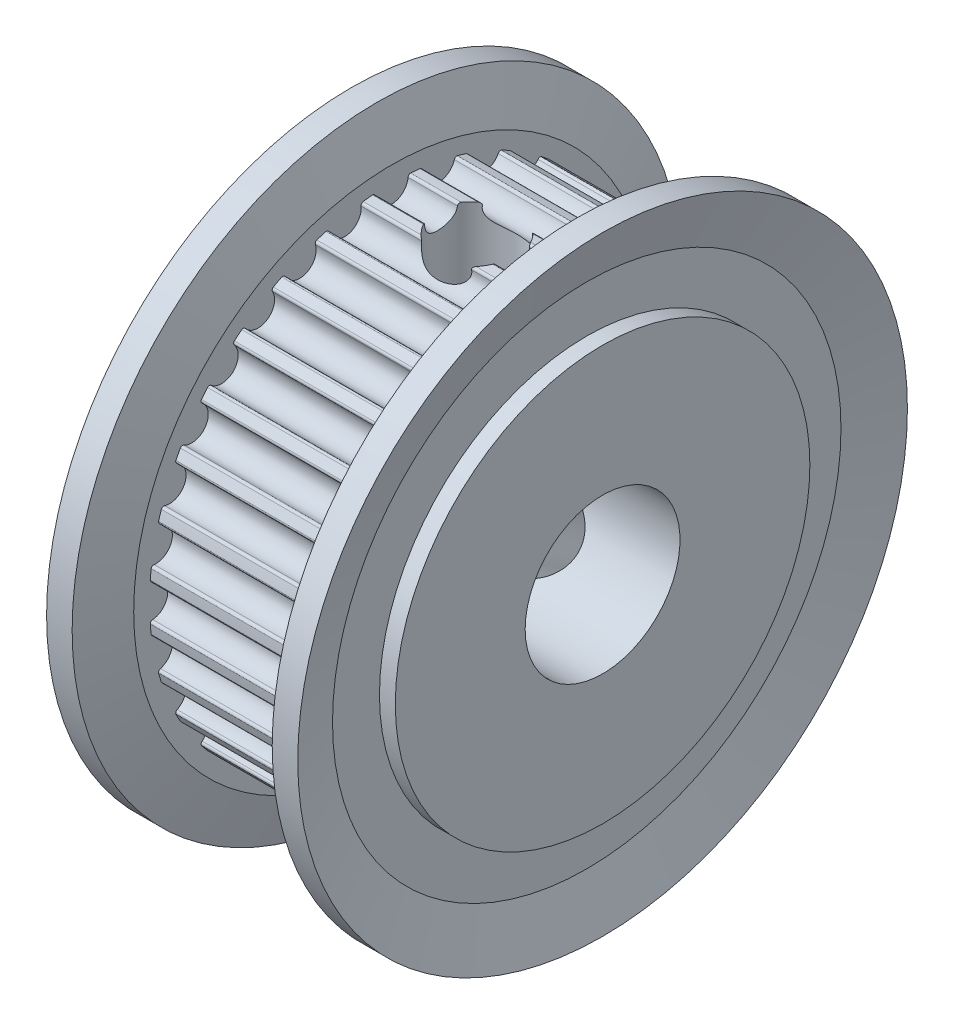
SolidWorks part; units mm, degrees
ref_plane "Front Plane" through (0, 0, 0) normal (0, 0, 1) x (1, 0, 0)
ref_plane "Top Plane" through (0, 0, 0) normal (0, 1, 0) x (1, 0, 0)
ref_plane "Right Plane" through (0, 0, 0) normal (1, 0, 0) x (0, 0, -1)
ref_plane "Plane1" through (0, 0, 0) normal (0, 0, 1) x (1, 0, 0)
sketch "Sketch1" plane through (0, 0, 0) normal (0, 0, 1) x (1, 0, 0)
  line L0 (-5.15, 0) -> (-5.15, 8.5)
  line L1 (-5.15, 8.5) -> (-3.5, 8.5)
  line L2 (-3.5, 8.5) -> (-3.5, 9.93)
  line L3 (-3.5, 9.93) -> (3.5, 9.93)
  line L4 (3.5, 9.93) -> (3.5, 8.5)
  line L5 (3.5, 8.5) -> (5.15, 8.5)
  line L6 (5.15, 8.5) -> (5.15, 0)
  line L7 (5.15, 0) -> (-5.15, 0)
  line L8 (5.15, 0) -> (-5.15, 0) construction
revolve "Revolve1" add sketch "Sketch1" angle 360 about L8
ref_plane "Plane2" through (0, 0, 0) normal (1, 0, 0) x (0, 0, -1)
sketch "Sketch2" plane through (0, 0, 0) normal (1, 0, 0) x (0, 0, -1)
  line L0 (-0.9509, 10.1405) -> (-0.9273, 9.8885)
  line L1 (-0.9273, 9.8885) -> (-0.793, 9.8993)
  line L2 (0.793, 9.8993) -> (0.9273, 9.8885)
  line L3 (0.9273, 9.8885) -> (0.9509, 10.1405)
  arc A0 (-0.793, 9.8993) -> (-0.6724, 9.7974) centre (-0.784, 9.7876) cw
  arc A1 (-0.6724, 9.7974) -> (0.6724, 9.7974) centre (0, 9.856) ccw
  arc A2 (0.6724, 9.7974) -> (0.793, 9.8993) centre (0.784, 9.7876) cw
  arc A3 (0.9509, 10.1405) -> (-0.9509, 10.1405) centre (0, 0) ccw
extrude "Cut-Extrude1" cut sketch "Sketch2" against normal blind 3.5 and the other way blind 3.5
ref_plane "Plane3" through (0, 0, 0) normal (1, 0, 0) x (0, 0, -1)
sketch "Sketch3" plane through (0, 0, 0) normal (1, 0, 0) x (0, 0, -1)
  line L0 (-2.911, 9.7602) -> (-2.8386, 9.5176)
  line L1 (-2.8386, 9.5176) -> (-2.709, 9.5544)
  line L2 (-1.1535, 9.8638) -> (-1.0197, 9.8794)
  line L3 (-1.0197, 9.8794) -> (-1.0457, 10.1312)
  arc A0 (-2.709, 9.5544) -> (-2.5709, 9.4779) centre (-2.6784, 9.4466) cw
  arc A1 (-2.5709, 9.4779) -> (-1.2518, 9.7403) centre (-1.9228, 9.6666) ccw
  arc A2 (-1.2518, 9.7403) -> (-1.1535, 9.8638) centre (-1.1405, 9.7525) cw
  arc A3 (-1.0457, 10.1312) -> (-2.911, 9.7602) centre (0, 0) ccw
extrude "Cut-Extrude2" cut sketch "Sketch3" against normal blind 3.5 and the other way blind 3.5
ref_plane "Plane4" through (0, 0, 0) normal (1, 0, 0) x (0, 0, -1)
sketch "Sketch4" plane through (0, 0, 0) normal (1, 0, 0) x (0, 0, -1)
  line L0 (-4.7591, 9.0047) -> (-4.6409, 8.781)
  line L1 (-4.6409, 8.781) -> (-4.5209, 8.8423)
  line L2 (-3.0557, 9.4492) -> (-2.9275, 9.4907)
  line L3 (-2.9275, 9.4907) -> (-3.0021, 9.7325)
  arc A0 (-4.5209, 8.8423) -> (-4.3706, 8.7943) centre (-4.4699, 8.7426) cw
  arc A1 (-4.3706, 8.7943) -> (-3.128, 9.3089) centre (-3.7717, 9.1058) ccw
  arc A2 (-3.128, 9.3089) -> (-3.0557, 9.4492) centre (-3.0212, 9.3426) cw
  arc A3 (-3.0021, 9.7325) -> (-4.7591, 9.0047) centre (0, 0) ccw
extrude "Cut-Extrude3" cut sketch "Sketch4" against normal blind 3.5 and the other way blind 3.5
ref_plane "Plane5" through (0, 0, 0) normal (1, 0, 0) x (0, 0, -1)
sketch "Sketch5" plane through (0, 0, 0) normal (1, 0, 0) x (0, 0, -1)
  line L0 (-6.4244, 7.9032) -> (-6.2648, 7.7068)
  line L1 (-6.2648, 7.7068) -> (-6.1591, 7.7904)
  line L2 (-4.8404, 8.6715) -> (-4.7228, 8.7372)
  line L3 (-4.7228, 8.7372) -> (-4.8431, 8.9598)
  arc A0 (-6.1591, 7.7904) -> (-6.0023, 7.7726) centre (-6.0896, 7.7026) cw
  arc A1 (-6.0023, 7.7726) -> (-4.884, 8.5198) centre (-5.4757, 8.195) ccw
  arc A2 (-4.884, 8.5198) -> (-4.8404, 8.6715) centre (-4.7858, 8.5737) cw
  arc A3 (-4.8431, 8.9598) -> (-6.4244, 7.9032) centre (0, 0) ccw
extrude "Cut-Extrude4" cut sketch "Sketch5" against normal blind 3.5 and the other way blind 3.5
ref_plane "Plane6" through (0, 0, 0) normal (1, 0, 0) x (0, 0, -1)
sketch "Sketch6" plane through (0, 0, 0) normal (1, 0, 0) x (0, 0, -1)
  line L0 (-7.8428, 6.498) -> (-7.6479, 6.3366)
  line L1 (-7.6479, 6.3366) -> (-7.5606, 6.4391)
  line L2 (-6.4391, 7.5606) -> (-6.3366, 7.6479)
  line L3 (-6.3366, 7.6479) -> (-6.498, 7.8428)
  arc A0 (-7.5606, 6.4391) -> (-7.4033, 6.4523) centre (-7.4753, 6.3665) cw
  arc A1 (-7.4033, 6.4523) -> (-6.4523, 7.4033) centre (-6.9692, 6.9692) ccw
  arc A2 (-6.4523, 7.4033) -> (-6.4391, 7.5606) centre (-6.3665, 7.4753) cw
  arc A3 (-6.498, 7.8428) -> (-7.8428, 6.498) centre (0, 0) ccw
extrude "Cut-Extrude5" cut sketch "Sketch6" against normal blind 3.5 and the other way blind 3.5
ref_plane "Plane7" through (0, 0, 0) normal (1, 0, 0) x (0, 0, -1)
sketch "Sketch7" plane through (0, 0, 0) normal (1, 0, 0) x (0, 0, -1)
  line L0 (-8.9598, 4.8431) -> (-8.7372, 4.7228)
  line L1 (-8.7372, 4.7228) -> (-8.6715, 4.8404)
  line L2 (-7.7904, 6.1591) -> (-7.7068, 6.2648)
  line L3 (-7.7068, 6.2648) -> (-7.9032, 6.4244)
  arc A0 (-8.6715, 4.8404) -> (-8.5198, 4.884) centre (-8.5737, 4.7858) cw
  arc A1 (-8.5198, 4.884) -> (-7.7726, 6.0023) centre (-8.195, 5.4757) ccw
  arc A2 (-7.7726, 6.0023) -> (-7.7904, 6.1591) centre (-7.7026, 6.0896) cw
  arc A3 (-7.9032, 6.4244) -> (-8.9598, 4.8431) centre (0, 0) ccw
extrude "Cut-Extrude6" cut sketch "Sketch7" against normal blind 3.5 and the other way blind 3.5
ref_plane "Plane8" through (0, 0, 0) normal (1, 0, 0) x (0, 0, -1)
sketch "Sketch8" plane through (0, 0, 0) normal (1, 0, 0) x (0, 0, -1)
  line L0 (-9.7325, 3.0021) -> (-9.4907, 2.9275)
  line L1 (-9.4907, 2.9275) -> (-9.4492, 3.0557)
  line L2 (-8.8423, 4.5209) -> (-8.781, 4.6409)
  line L3 (-8.781, 4.6409) -> (-9.0047, 4.7591)
  arc A0 (-9.4492, 3.0557) -> (-9.3089, 3.128) centre (-9.3426, 3.0212) cw
  arc A1 (-9.3089, 3.128) -> (-8.7943, 4.3706) centre (-9.1058, 3.7717) ccw
  arc A2 (-8.7943, 4.3706) -> (-8.8423, 4.5209) centre (-8.7426, 4.4699) cw
  arc A3 (-9.0047, 4.7591) -> (-9.7325, 3.0021) centre (0, 0) ccw
extrude "Cut-Extrude7" cut sketch "Sketch8" against normal blind 3.5 and the other way blind 3.5
ref_plane "Plane9" through (0, 0, 0) normal (1, 0, 0) x (0, 0, -1)
sketch "Sketch9" plane through (0, 0, 0) normal (1, 0, 0) x (0, 0, -1)
  line L0 (-10.1312, 1.0457) -> (-9.8794, 1.0197)
  line L1 (-9.8794, 1.0197) -> (-9.8638, 1.1535)
  line L2 (-9.5544, 2.709) -> (-9.5176, 2.8386)
  line L3 (-9.5176, 2.8386) -> (-9.7602, 2.911)
  arc A0 (-9.8638, 1.1535) -> (-9.7403, 1.2518) centre (-9.7525, 1.1405) cw
  arc A1 (-9.7403, 1.2518) -> (-9.4779, 2.5709) centre (-9.6666, 1.9228) ccw
  arc A2 (-9.4779, 2.5709) -> (-9.5544, 2.709) centre (-9.4466, 2.6784) cw
  arc A3 (-9.7602, 2.911) -> (-10.1312, 1.0457) centre (0, 0) ccw
extrude "Cut-Extrude8" cut sketch "Sketch9" against normal blind 3.5 and the other way blind 3.5
ref_plane "Plane10" through (0, 0, 0) normal (1, 0, 0) x (0, 0, -1)
sketch "Sketch10" plane through (0, 0, 0) normal (1, 0, 0) x (0, 0, -1)
  line L0 (-10.1405, -0.9509) -> (-9.8885, -0.9273)
  line L1 (-9.8885, -0.9273) -> (-9.8993, -0.793)
  line L2 (-9.8993, 0.793) -> (-9.8885, 0.9273)
  line L3 (-9.8885, 0.9273) -> (-10.1405, 0.9509)
  arc A0 (-9.8993, -0.793) -> (-9.7974, -0.6724) centre (-9.7876, -0.784) cw
  arc A1 (-9.7974, -0.6724) -> (-9.7974, 0.6724) centre (-9.856, 0) ccw
  arc A2 (-9.7974, 0.6724) -> (-9.8993, 0.793) centre (-9.7876, 0.784) cw
  arc A3 (-10.1405, 0.9509) -> (-10.1405, -0.9509) centre (0, 0) ccw
extrude "Cut-Extrude9" cut sketch "Sketch10" against normal blind 3.5 and the other way blind 3.5
ref_plane "Plane11" through (0, 0, 0) normal (1, 0, 0) x (0, 0, -1)
sketch "Sketch11" plane through (0, 0, 0) normal (1, 0, 0) x (0, 0, -1)
  line L0 (-9.7602, -2.911) -> (-9.5176, -2.8386)
  line L1 (-9.5176, -2.8386) -> (-9.5544, -2.709)
  line L2 (-9.8638, -1.1535) -> (-9.8794, -1.0197)
  line L3 (-9.8794, -1.0197) -> (-10.1312, -1.0457)
  arc A0 (-9.5544, -2.709) -> (-9.4779, -2.5709) centre (-9.4466, -2.6784) cw
  arc A1 (-9.4779, -2.5709) -> (-9.7403, -1.2518) centre (-9.6666, -1.9228) ccw
  arc A2 (-9.7403, -1.2518) -> (-9.8638, -1.1535) centre (-9.7525, -1.1405) cw
  arc A3 (-10.1312, -1.0457) -> (-9.7602, -2.911) centre (0, 0) ccw
extrude "Cut-Extrude10" cut sketch "Sketch11" against normal blind 3.5 and the other way blind 3.5
ref_plane "Plane12" through (0, 0, 0) normal (1, 0, 0) x (0, 0, -1)
sketch "Sketch12" plane through (0, 0, 0) normal (1, 0, 0) x (0, 0, -1)
  line L0 (-9.0047, -4.7591) -> (-8.781, -4.6409)
  line L1 (-8.781, -4.6409) -> (-8.8423, -4.5209)
  line L2 (-9.4492, -3.0557) -> (-9.4907, -2.9275)
  line L3 (-9.4907, -2.9275) -> (-9.7325, -3.0021)
  arc A0 (-8.8423, -4.5209) -> (-8.7943, -4.3706) centre (-8.7426, -4.4699) cw
  arc A1 (-8.7943, -4.3706) -> (-9.3089, -3.128) centre (-9.1058, -3.7717) ccw
  arc A2 (-9.3089, -3.128) -> (-9.4492, -3.0557) centre (-9.3426, -3.0212) cw
  arc A3 (-9.7325, -3.0021) -> (-9.0047, -4.7591) centre (0, 0) ccw
extrude "Cut-Extrude11" cut sketch "Sketch12" against normal blind 3.5 and the other way blind 3.5
ref_plane "Plane13" through (0, 0, 0) normal (1, 0, 0) x (0, 0, -1)
sketch "Sketch13" plane through (0, 0, 0) normal (1, 0, 0) x (0, 0, -1)
  line L0 (-7.9032, -6.4244) -> (-7.7068, -6.2648)
  line L1 (-7.7068, -6.2648) -> (-7.7904, -6.1591)
  line L2 (-8.6715, -4.8404) -> (-8.7372, -4.7228)
  line L3 (-8.7372, -4.7228) -> (-8.9598, -4.8431)
  arc A0 (-7.7904, -6.1591) -> (-7.7726, -6.0023) centre (-7.7026, -6.0896) cw
  arc A1 (-7.7726, -6.0023) -> (-8.5198, -4.884) centre (-8.195, -5.4757) ccw
  arc A2 (-8.5198, -4.884) -> (-8.6715, -4.8404) centre (-8.5737, -4.7858) cw
  arc A3 (-8.9598, -4.8431) -> (-7.9032, -6.4244) centre (0, 0) ccw
extrude "Cut-Extrude12" cut sketch "Sketch13" against normal blind 3.5 and the other way blind 3.5
ref_plane "Plane14" through (0, 0, 0) normal (1, 0, 0) x (0, 0, -1)
sketch "Sketch14" plane through (0, 0, 0) normal (1, 0, 0) x (0, 0, -1)
  line L0 (-6.498, -7.8428) -> (-6.3366, -7.6479)
  line L1 (-6.3366, -7.6479) -> (-6.4391, -7.5606)
  line L2 (-7.5606, -6.4391) -> (-7.6479, -6.3366)
  line L3 (-7.6479, -6.3366) -> (-7.8428, -6.498)
  arc A0 (-6.4391, -7.5606) -> (-6.4523, -7.4033) centre (-6.3665, -7.4753) cw
  arc A1 (-6.4523, -7.4033) -> (-7.4033, -6.4523) centre (-6.9692, -6.9692) ccw
  arc A2 (-7.4033, -6.4523) -> (-7.5606, -6.4391) centre (-7.4753, -6.3665) cw
  arc A3 (-7.8428, -6.498) -> (-6.498, -7.8428) centre (0, 0) ccw
extrude "Cut-Extrude13" cut sketch "Sketch14" against normal blind 3.5 and the other way blind 3.5
ref_plane "Plane15" through (0, 0, 0) normal (1, 0, 0) x (0, 0, -1)
sketch "Sketch15" plane through (0, 0, 0) normal (1, 0, 0) x (0, 0, -1)
  line L0 (-4.8431, -8.9598) -> (-4.7228, -8.7372)
  line L1 (-4.7228, -8.7372) -> (-4.8404, -8.6715)
  line L2 (-6.1591, -7.7904) -> (-6.2648, -7.7068)
  line L3 (-6.2648, -7.7068) -> (-6.4244, -7.9032)
  arc A0 (-4.8404, -8.6715) -> (-4.884, -8.5198) centre (-4.7858, -8.5737) cw
  arc A1 (-4.884, -8.5198) -> (-6.0023, -7.7726) centre (-5.4757, -8.195) ccw
  arc A2 (-6.0023, -7.7726) -> (-6.1591, -7.7904) centre (-6.0896, -7.7026) cw
  arc A3 (-6.4244, -7.9032) -> (-4.8431, -8.9598) centre (0, 0) ccw
extrude "Cut-Extrude14" cut sketch "Sketch15" against normal blind 3.5 and the other way blind 3.5
ref_plane "Plane16" through (0, 0, 0) normal (1, 0, 0) x (0, 0, -1)
sketch "Sketch16" plane through (0, 0, 0) normal (1, 0, 0) x (0, 0, -1)
  line L0 (-3.0021, -9.7325) -> (-2.9275, -9.4907)
  line L1 (-2.9275, -9.4907) -> (-3.0557, -9.4492)
  line L2 (-4.5209, -8.8423) -> (-4.6409, -8.781)
  line L3 (-4.6409, -8.781) -> (-4.7591, -9.0047)
  arc A0 (-3.0557, -9.4492) -> (-3.128, -9.3089) centre (-3.0212, -9.3426) cw
  arc A1 (-3.128, -9.3089) -> (-4.3706, -8.7943) centre (-3.7717, -9.1058) ccw
  arc A2 (-4.3706, -8.7943) -> (-4.5209, -8.8423) centre (-4.4699, -8.7426) cw
  arc A3 (-4.7591, -9.0047) -> (-3.0021, -9.7325) centre (0, 0) ccw
extrude "Cut-Extrude15" cut sketch "Sketch16" against normal blind 3.5 and the other way blind 3.5
ref_plane "Plane17" through (0, 0, 0) normal (1, 0, 0) x (0, 0, -1)
sketch "Sketch17" plane through (0, 0, 0) normal (1, 0, 0) x (0, 0, -1)
  line L0 (-1.0457, -10.1312) -> (-1.0197, -9.8794)
  line L1 (-1.0197, -9.8794) -> (-1.1535, -9.8638)
  line L2 (-2.709, -9.5544) -> (-2.8386, -9.5176)
  line L3 (-2.8386, -9.5176) -> (-2.911, -9.7602)
  arc A0 (-1.1535, -9.8638) -> (-1.2518, -9.7403) centre (-1.1405, -9.7525) cw
  arc A1 (-1.2518, -9.7403) -> (-2.5709, -9.4779) centre (-1.9228, -9.6666) ccw
  arc A2 (-2.5709, -9.4779) -> (-2.709, -9.5544) centre (-2.6784, -9.4466) cw
  arc A3 (-2.911, -9.7602) -> (-1.0457, -10.1312) centre (0, 0) ccw
extrude "Cut-Extrude16" cut sketch "Sketch17" against normal blind 3.5 and the other way blind 3.5
ref_plane "Plane18" through (0, 0, 0) normal (1, 0, 0) x (0, 0, -1)
sketch "Sketch18" plane through (0, 0, 0) normal (1, 0, 0) x (0, 0, -1)
  line L0 (0.9509, -10.1405) -> (0.9273, -9.8885)
  line L1 (0.9273, -9.8885) -> (0.793, -9.8993)
  line L2 (-0.793, -9.8993) -> (-0.9273, -9.8885)
  line L3 (-0.9273, -9.8885) -> (-0.9509, -10.1405)
  arc A0 (0.793, -9.8993) -> (0.6724, -9.7974) centre (0.784, -9.7876) cw
  arc A1 (0.6724, -9.7974) -> (-0.6724, -9.7974) centre (0, -9.856) ccw
  arc A2 (-0.6724, -9.7974) -> (-0.793, -9.8993) centre (-0.784, -9.7876) cw
  arc A3 (-0.9509, -10.1405) -> (0.9509, -10.1405) centre (0, 0) ccw
extrude "Cut-Extrude17" cut sketch "Sketch18" against normal blind 3.5 and the other way blind 3.5
ref_plane "Plane19" through (0, 0, 0) normal (1, 0, 0) x (0, 0, -1)
sketch "Sketch19" plane through (0, 0, 0) normal (1, 0, 0) x (0, 0, -1)
  line L0 (2.911, -9.7602) -> (2.8386, -9.5176)
  line L1 (2.8386, -9.5176) -> (2.709, -9.5544)
  line L2 (1.1535, -9.8638) -> (1.0197, -9.8794)
  line L3 (1.0197, -9.8794) -> (1.0457, -10.1312)
  arc A0 (2.709, -9.5544) -> (2.5709, -9.4779) centre (2.6784, -9.4466) cw
  arc A1 (2.5709, -9.4779) -> (1.2518, -9.7403) centre (1.9228, -9.6666) ccw
  arc A2 (1.2518, -9.7403) -> (1.1535, -9.8638) centre (1.1405, -9.7525) cw
  arc A3 (1.0457, -10.1312) -> (2.911, -9.7602) centre (0, 0) ccw
extrude "Cut-Extrude18" cut sketch "Sketch19" against normal blind 3.5 and the other way blind 3.5
ref_plane "Plane20" through (0, 0, 0) normal (1, 0, 0) x (0, 0, -1)
sketch "Sketch20" plane through (0, 0, 0) normal (1, 0, 0) x (0, 0, -1)
  line L0 (4.7591, -9.0047) -> (4.6409, -8.781)
  line L1 (4.6409, -8.781) -> (4.5209, -8.8423)
  line L2 (3.0557, -9.4492) -> (2.9275, -9.4907)
  line L3 (2.9275, -9.4907) -> (3.0021, -9.7325)
  arc A0 (4.5209, -8.8423) -> (4.3706, -8.7943) centre (4.4699, -8.7426) cw
  arc A1 (4.3706, -8.7943) -> (3.128, -9.3089) centre (3.7717, -9.1058) ccw
  arc A2 (3.128, -9.3089) -> (3.0557, -9.4492) centre (3.0212, -9.3426) cw
  arc A3 (3.0021, -9.7325) -> (4.7591, -9.0047) centre (0, 0) ccw
extrude "Cut-Extrude19" cut sketch "Sketch20" against normal blind 3.5 and the other way blind 3.5
ref_plane "Plane21" through (0, 0, 0) normal (1, 0, 0) x (0, 0, -1)
sketch "Sketch21" plane through (0, 0, 0) normal (1, 0, 0) x (0, 0, -1)
  line L0 (6.4244, -7.9032) -> (6.2648, -7.7068)
  line L1 (6.2648, -7.7068) -> (6.1591, -7.7904)
  line L2 (4.8404, -8.6715) -> (4.7228, -8.7372)
  line L3 (4.7228, -8.7372) -> (4.8431, -8.9598)
  arc A0 (6.1591, -7.7904) -> (6.0023, -7.7726) centre (6.0896, -7.7026) cw
  arc A1 (6.0023, -7.7726) -> (4.884, -8.5198) centre (5.4757, -8.195) ccw
  arc A2 (4.884, -8.5198) -> (4.8404, -8.6715) centre (4.7858, -8.5737) cw
  arc A3 (4.8431, -8.9598) -> (6.4244, -7.9032) centre (0, 0) ccw
extrude "Cut-Extrude20" cut sketch "Sketch21" against normal blind 3.5 and the other way blind 3.5
ref_plane "Plane22" through (0, 0, 0) normal (1, 0, 0) x (0, 0, -1)
sketch "Sketch22" plane through (0, 0, 0) normal (1, 0, 0) x (0, 0, -1)
  line L0 (7.8428, -6.498) -> (7.6479, -6.3366)
  line L1 (7.6479, -6.3366) -> (7.5606, -6.4391)
  line L2 (6.4391, -7.5606) -> (6.3366, -7.6479)
  line L3 (6.3366, -7.6479) -> (6.498, -7.8428)
  arc A0 (7.5606, -6.4391) -> (7.4033, -6.4523) centre (7.4753, -6.3665) cw
  arc A1 (7.4033, -6.4523) -> (6.4523, -7.4033) centre (6.9692, -6.9692) ccw
  arc A2 (6.4523, -7.4033) -> (6.4391, -7.5606) centre (6.3665, -7.4753) cw
  arc A3 (6.498, -7.8428) -> (7.8428, -6.498) centre (0, 0) ccw
extrude "Cut-Extrude21" cut sketch "Sketch22" against normal blind 3.5 and the other way blind 3.5
ref_plane "Plane23" through (0, 0, 0) normal (1, 0, 0) x (0, 0, -1)
sketch "Sketch23" plane through (0, 0, 0) normal (1, 0, 0) x (0, 0, -1)
  line L0 (8.9598, -4.8431) -> (8.7372, -4.7228)
  line L1 (8.7372, -4.7228) -> (8.6715, -4.8404)
  line L2 (7.7904, -6.1591) -> (7.7068, -6.2648)
  line L3 (7.7068, -6.2648) -> (7.9032, -6.4244)
  arc A0 (8.6715, -4.8404) -> (8.5198, -4.884) centre (8.5737, -4.7858) cw
  arc A1 (8.5198, -4.884) -> (7.7726, -6.0023) centre (8.195, -5.4757) ccw
  arc A2 (7.7726, -6.0023) -> (7.7904, -6.1591) centre (7.7026, -6.0896) cw
  arc A3 (7.9032, -6.4244) -> (8.9598, -4.8431) centre (0, 0) ccw
extrude "Cut-Extrude22" cut sketch "Sketch23" against normal blind 3.5 and the other way blind 3.5
ref_plane "Plane24" through (0, 0, 0) normal (1, 0, 0) x (0, 0, -1)
sketch "Sketch24" plane through (0, 0, 0) normal (1, 0, 0) x (0, 0, -1)
  line L0 (9.7325, -3.0021) -> (9.4907, -2.9275)
  line L1 (9.4907, -2.9275) -> (9.4492, -3.0557)
  line L2 (8.8423, -4.5209) -> (8.781, -4.6409)
  line L3 (8.781, -4.6409) -> (9.0047, -4.7591)
  arc A0 (9.4492, -3.0557) -> (9.3089, -3.128) centre (9.3426, -3.0212) cw
  arc A1 (9.3089, -3.128) -> (8.7943, -4.3706) centre (9.1058, -3.7717) ccw
  arc A2 (8.7943, -4.3706) -> (8.8423, -4.5209) centre (8.7426, -4.4699) cw
  arc A3 (9.0047, -4.7591) -> (9.7325, -3.0021) centre (0, 0) ccw
extrude "Cut-Extrude23" cut sketch "Sketch24" against normal blind 3.5 and the other way blind 3.5
ref_plane "Plane25" through (0, 0, 0) normal (1, 0, 0) x (0, 0, -1)
sketch "Sketch25" plane through (0, 0, 0) normal (1, 0, 0) x (0, 0, -1)
  line L0 (10.1312, -1.0457) -> (9.8794, -1.0197)
  line L1 (9.8794, -1.0197) -> (9.8638, -1.1535)
  line L2 (9.5544, -2.709) -> (9.5176, -2.8386)
  line L3 (9.5176, -2.8386) -> (9.7602, -2.911)
  arc A0 (9.8638, -1.1535) -> (9.7403, -1.2518) centre (9.7525, -1.1405) cw
  arc A1 (9.7403, -1.2518) -> (9.4779, -2.5709) centre (9.6666, -1.9228) ccw
  arc A2 (9.4779, -2.5709) -> (9.5544, -2.709) centre (9.4466, -2.6784) cw
  arc A3 (9.7602, -2.911) -> (10.1312, -1.0457) centre (0, 0) ccw
extrude "Cut-Extrude24" cut sketch "Sketch25" against normal blind 3.5 and the other way blind 3.5
ref_plane "Plane26" through (0, 0, 0) normal (1, 0, 0) x (0, 0, -1)
sketch "Sketch26" plane through (0, 0, 0) normal (1, 0, 0) x (0, 0, -1)
  line L0 (10.1405, 0.9509) -> (9.8885, 0.9273)
  line L1 (9.8885, 0.9273) -> (9.8993, 0.793)
  line L2 (9.8993, -0.793) -> (9.8885, -0.9273)
  line L3 (9.8885, -0.9273) -> (10.1405, -0.9509)
  arc A0 (9.8993, 0.793) -> (9.7974, 0.6724) centre (9.7876, 0.784) cw
  arc A1 (9.7974, 0.6724) -> (9.7974, -0.6724) centre (9.856, 0) ccw
  arc A2 (9.7974, -0.6724) -> (9.8993, -0.793) centre (9.7876, -0.784) cw
  arc A3 (10.1405, -0.9509) -> (10.1405, 0.9509) centre (0, 0) ccw
extrude "Cut-Extrude25" cut sketch "Sketch26" against normal blind 3.5 and the other way blind 3.5
ref_plane "Plane27" through (0, 0, 0) normal (1, 0, 0) x (0, 0, -1)
sketch "Sketch27" plane through (0, 0, 0) normal (1, 0, 0) x (0, 0, -1)
  line L0 (9.7602, 2.911) -> (9.5176, 2.8386)
  line L1 (9.5176, 2.8386) -> (9.5544, 2.709)
  line L2 (9.8638, 1.1535) -> (9.8794, 1.0197)
  line L3 (9.8794, 1.0197) -> (10.1312, 1.0457)
  arc A0 (9.5544, 2.709) -> (9.4779, 2.5709) centre (9.4466, 2.6784) cw
  arc A1 (9.4779, 2.5709) -> (9.7403, 1.2518) centre (9.6666, 1.9228) ccw
  arc A2 (9.7403, 1.2518) -> (9.8638, 1.1535) centre (9.7525, 1.1405) cw
  arc A3 (10.1312, 1.0457) -> (9.7602, 2.911) centre (0, 0) ccw
extrude "Cut-Extrude26" cut sketch "Sketch27" against normal blind 3.5 and the other way blind 3.5
ref_plane "Plane28" through (0, 0, 0) normal (1, 0, 0) x (0, 0, -1)
sketch "Sketch28" plane through (0, 0, 0) normal (1, 0, 0) x (0, 0, -1)
  line L0 (9.0047, 4.7591) -> (8.781, 4.6409)
  line L1 (8.781, 4.6409) -> (8.8423, 4.5209)
  line L2 (9.4492, 3.0557) -> (9.4907, 2.9275)
  line L3 (9.4907, 2.9275) -> (9.7325, 3.0021)
  arc A0 (8.8423, 4.5209) -> (8.7943, 4.3706) centre (8.7426, 4.4699) cw
  arc A1 (8.7943, 4.3706) -> (9.3089, 3.128) centre (9.1058, 3.7717) ccw
  arc A2 (9.3089, 3.128) -> (9.4492, 3.0557) centre (9.3426, 3.0212) cw
  arc A3 (9.7325, 3.0021) -> (9.0047, 4.7591) centre (0, 0) ccw
extrude "Cut-Extrude27" cut sketch "Sketch28" against normal blind 3.5 and the other way blind 3.5
ref_plane "Plane29" through (0, 0, 0) normal (1, 0, 0) x (0, 0, -1)
sketch "Sketch29" plane through (0, 0, 0) normal (1, 0, 0) x (0, 0, -1)
  line L0 (7.9032, 6.4244) -> (7.7068, 6.2648)
  line L1 (7.7068, 6.2648) -> (7.7904, 6.1591)
  line L2 (8.6715, 4.8404) -> (8.7372, 4.7228)
  line L3 (8.7372, 4.7228) -> (8.9598, 4.8431)
  arc A0 (7.7904, 6.1591) -> (7.7726, 6.0023) centre (7.7026, 6.0896) cw
  arc A1 (7.7726, 6.0023) -> (8.5198, 4.884) centre (8.195, 5.4757) ccw
  arc A2 (8.5198, 4.884) -> (8.6715, 4.8404) centre (8.5737, 4.7858) cw
  arc A3 (8.9598, 4.8431) -> (7.9032, 6.4244) centre (0, 0) ccw
extrude "Cut-Extrude28" cut sketch "Sketch29" against normal blind 3.5 and the other way blind 3.5
ref_plane "Plane30" through (0, 0, 0) normal (1, 0, 0) x (0, 0, -1)
sketch "Sketch30" plane through (0, 0, 0) normal (1, 0, 0) x (0, 0, -1)
  line L0 (6.498, 7.8428) -> (6.3366, 7.6479)
  line L1 (6.3366, 7.6479) -> (6.4391, 7.5606)
  line L2 (7.5606, 6.4391) -> (7.6479, 6.3366)
  line L3 (7.6479, 6.3366) -> (7.8428, 6.498)
  arc A0 (6.4391, 7.5606) -> (6.4523, 7.4033) centre (6.3665, 7.4753) cw
  arc A1 (6.4523, 7.4033) -> (7.4033, 6.4523) centre (6.9692, 6.9692) ccw
  arc A2 (7.4033, 6.4523) -> (7.5606, 6.4391) centre (7.4753, 6.3665) cw
  arc A3 (7.8428, 6.498) -> (6.498, 7.8428) centre (0, 0) ccw
extrude "Cut-Extrude29" cut sketch "Sketch30" against normal blind 3.5 and the other way blind 3.5
ref_plane "Plane31" through (0, 0, 0) normal (1, 0, 0) x (0, 0, -1)
sketch "Sketch31" plane through (0, 0, 0) normal (1, 0, 0) x (0, 0, -1)
  line L0 (4.8431, 8.9598) -> (4.7228, 8.7372)
  line L1 (4.7228, 8.7372) -> (4.8404, 8.6715)
  line L2 (6.1591, 7.7904) -> (6.2648, 7.7068)
  line L3 (6.2648, 7.7068) -> (6.4244, 7.9032)
  arc A0 (4.8404, 8.6715) -> (4.884, 8.5198) centre (4.7858, 8.5737) cw
  arc A1 (4.884, 8.5198) -> (6.0023, 7.7726) centre (5.4757, 8.195) ccw
  arc A2 (6.0023, 7.7726) -> (6.1591, 7.7904) centre (6.0896, 7.7026) cw
  arc A3 (6.4244, 7.9032) -> (4.8431, 8.9598) centre (0, 0) ccw
extrude "Cut-Extrude30" cut sketch "Sketch31" against normal blind 3.5 and the other way blind 3.5
ref_plane "Plane32" through (0, 0, 0) normal (1, 0, 0) x (0, 0, -1)
sketch "Sketch32" plane through (0, 0, 0) normal (1, 0, 0) x (0, 0, -1)
  line L0 (3.0021, 9.7325) -> (2.9275, 9.4907)
  line L1 (2.9275, 9.4907) -> (3.0557, 9.4492)
  line L2 (4.5209, 8.8423) -> (4.6409, 8.781)
  line L3 (4.6409, 8.781) -> (4.7591, 9.0047)
  arc A0 (3.0557, 9.4492) -> (3.128, 9.3089) centre (3.0212, 9.3426) cw
  arc A1 (3.128, 9.3089) -> (4.3706, 8.7943) centre (3.7717, 9.1058) ccw
  arc A2 (4.3706, 8.7943) -> (4.5209, 8.8423) centre (4.4699, 8.7426) cw
  arc A3 (4.7591, 9.0047) -> (3.0021, 9.7325) centre (0, 0) ccw
extrude "Cut-Extrude31" cut sketch "Sketch32" against normal blind 3.5 and the other way blind 3.5
ref_plane "Plane33" through (0, 0, 0) normal (1, 0, 0) x (0, 0, -1)
sketch "Sketch33" plane through (0, 0, 0) normal (1, 0, 0) x (0, 0, -1)
  line L0 (1.0457, 10.1312) -> (1.0197, 9.8794)
  line L1 (1.0197, 9.8794) -> (1.1535, 9.8638)
  line L2 (2.709, 9.5544) -> (2.8386, 9.5176)
  line L3 (2.8386, 9.5176) -> (2.911, 9.7602)
  arc A0 (1.1535, 9.8638) -> (1.2518, 9.7403) centre (1.1405, 9.7525) cw
  arc A1 (1.2518, 9.7403) -> (2.5709, 9.4779) centre (1.9228, 9.6666) ccw
  arc A2 (2.5709, 9.4779) -> (2.709, 9.5544) centre (2.6784, 9.4466) cw
  arc A3 (2.911, 9.7602) -> (1.0457, 10.1312) centre (0, 0) ccw
extrude "Cut-Extrude32" cut sketch "Sketch33" against normal blind 3.5 and the other way blind 3.5
ref_plane "Plane34" through (0, 0, 0) normal (0, 0, 1) x (1, 0, 0)
sketch "Sketch34" plane through (0, 0, 0) normal (0, 0, 1) x (1, 0, 0)
  line L0 (3.5, 8.5) -> (4.5, 8.5)
  line L1 (4.5, 8.5) -> (4.5, 10.425)
  line L2 (4.5, 10.425) -> (5.15, 12.5)
  line L3 (5.15, 12.5) -> (4.1021, 12.5)
  line L4 (4.1021, 12.5) -> (3.5, 10.578)
  line L5 (3.5, 10.578) -> (3.5, 8.5)
  line L6 (50, 0) -> (-50, 0) construction
revolve "Revolve2" add sketch "Sketch34" angle 360 about L6
ref_plane "Plane35" through (0, 0, 0) normal (0, 0, 1) x (1, 0, 0)
sketch "Sketch35" plane through (0, 0, 0) normal (0, 0, 1) x (1, 0, 0)
  line L0 (-5.15, 12.5) -> (-4.5, 10.425)
  line L1 (-4.5, 10.425) -> (-4.5, 8.5)
  line L2 (-4.5, 8.5) -> (-3.5, 8.5)
  line L3 (-3.5, 8.5) -> (-3.5, 10.578)
  line L4 (-3.5, 10.578) -> (-4.1021, 12.5)
  line L5 (-4.1021, 12.5) -> (-5.15, 12.5)
  line L6 (50, 0) -> (-50, 0) construction
revolve "Revolve3" add sketch "Sketch35" angle 360 about L6
ref_plane "Plane36" through (0, 0, 0) normal (0, 0, 1) x (1, 0, 0)
sketch "Sketch36" plane through (0, 0, 0) normal (0, 0, 1) x (1, 0, 0)
  line L0 (-5.15, 0) -> (-5.15, 3.175)
  line L1 (-5.15, 3.175) -> (5.15, 3.175)
  line L2 (5.15, 3.175) -> (5.15, 0)
  line L3 (5.15, 0) -> (-5.15, 0)
  line L4 (5.15, 0) -> (-5.15, 0) construction
revolve "Cut-Revolve1" cut sketch "Sketch36" angle 360 about L4
ref_plane "Plane37" through (0, 0, 0) normal (1, 0, 0) x (0, 0, -1)
sketch "Sketch37" plane through (0, 0, 0) normal (1, 0, 0) x (0, 0, -1)
  line L0 (0, 9.93) -> (1.621, 9.93)
  line L1 (1.621, 9.93) -> (1.621, 0)
  line L2 (1.621, 0) -> (0, 0)
  line L3 (0, 0) -> (0, 9.93)
  line L4 (0, 0) -> (0, 9.93) construction
revolve "Cut-Revolve2" cut sketch "Sketch37" angle 360 about L4
ref_plane "Plane38" through (0, 0, 0) normal (1, 0, 0) x (0, 0, -1)
sketch "Sketch38" plane through (0, 0, 0) normal (1, 0, 0) x (0, 0, -1)
  line L0 (8.2565, -5.5168) -> (7.3559, -6.8646)
  line L1 (7.3559, -6.8646) -> (-0.9006, -1.3478)
  line L2 (-0.9006, -1.3478) -> (0, 0)
  line L3 (0, 0) -> (8.2565, -5.5168)
  line L4 (0, 0) -> (8.2565, -5.5168) construction
revolve "Cut-Revolve3" cut sketch "Sketch38" angle 360 about L4
